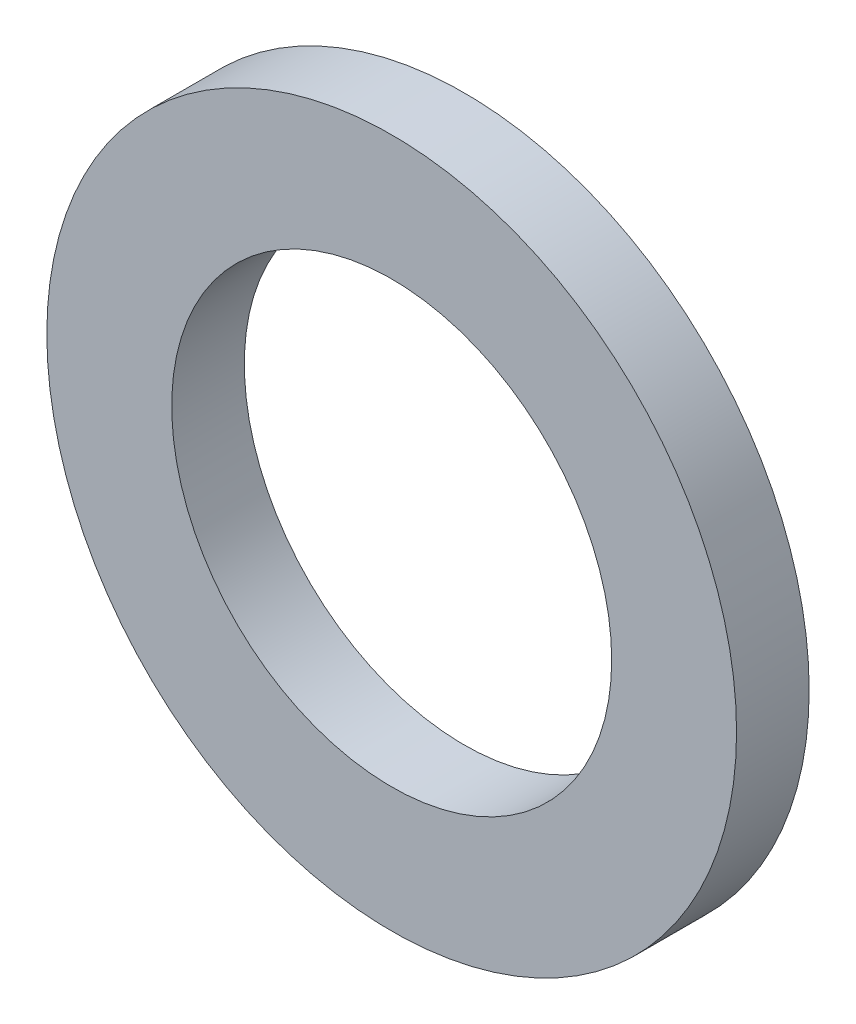
SolidWorks part; units mm, degrees
ref_plane "Piano frontale" through (0, 0, 0) normal (0, 0, 1) x (1, 0, 0)
ref_plane "Piano superiore" through (0, 0, 0) normal (0, 1, 0) x (1, 0, 0)
ref_plane "Piano destro" through (0, 0, 0) normal (1, 0, 0) x (0, 0, -1)
sketch "Schizzo1" plane through (0, 0, 0) normal (0, 0, 1) x (1, 0, 0)
  circle A0 centre (0, 0) radius 3.03
  circle A1 centre (0, 0) radius 4.75
  dimension "D1" = 6.06
  dimension "D2" = 9.5
extrude "Estrusione-Estrusione1" add sketch "Schizzo1" along normal blind 1
